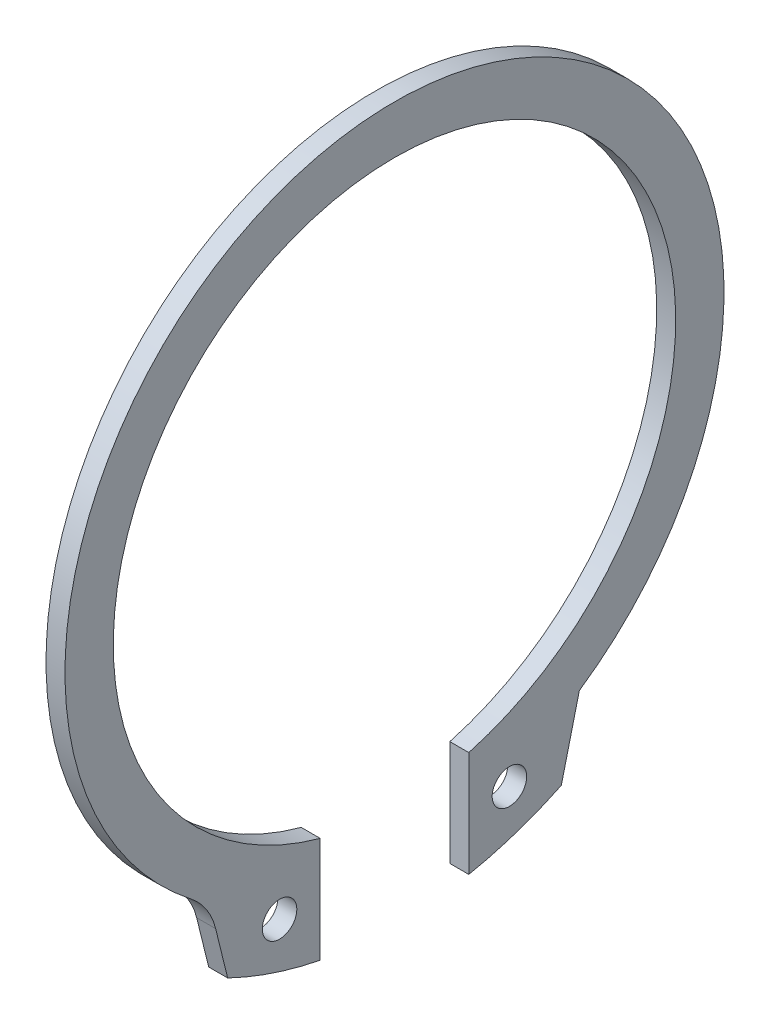
SolidWorks part; units mm, degrees
ref_plane "Front" through (0, 0, 0) normal (0, 0, 1) x (1, 0, 0)
ref_plane "Top" through (0, 0, 0) normal (0, 1, 0) x (1, 0, 0)
ref_plane "Right" through (0, 0, 0) normal (1, 0, 0) x (0, 0, -1)
sketch "Esquisse1" plane through (0, 0, 0) normal (1, 0, 0) x (0, 0, -1)
  line L0 (0, 0) -> (-10.7663, -39.302) construction
  line L1 (0, 0) -> (0, -72.5729) construction
  line L2 (-10.7663, -39.302) -> (-10.7663, -54.5964)
  line L3 (10.7663, -39.302) -> (10.7663, -54.5964)
  line L4 (-24.1737, -50.123) -> (-25.9166, -43.0571)
  line L5 (24.1737, -50.123) -> (26.7869, -39.5288)
  arc A1 (10.7663, -39.302) -> (-10.7663, -39.302) centre (0, 0) ccw
  arc A2 (26.7869, -39.5288) -> (-29.4566, -37.5815) centre (0, 0) ccw
  arc A4 (24.1737, -50.123) -> (10.7663, -54.5964) centre (0, 0) cw
  arc A5 (-24.1737, -50.123) -> (-10.7663, -54.5964) centre (0, 0) ccw
  circle A6 centre (-16.6536, -46.5046) radius 2.5
  circle A7 centre (16.6536, -46.5046) radius 2.5
  arc A8 (-25.9166, -43.0571) -> (-29.4566, -37.5815) centre (-35.6256, -45.452) ccw
  arc A9 (25.9166, -43.0571) -> (29.4566, -37.5815) centre (35.6256, -45.452) cw
  point P10 (10.7663, -39.302)
  point P13 (-24.1737, -50.123)
  point P20 (-26.7869, -39.5288)
  point P24 (-16.6536, -46.5046)
  dimension "D1" = 5
  dimension "D2" = 81.5
  dimension "D3" = 10
  dimension "D4" = 7
extrude "Boss.-Extru.1" add sketch "Esquisse1" along normal blind 2.75 contours A8 L4 A5 L2 A1 L3 A4 L5 A2 A6 A7
